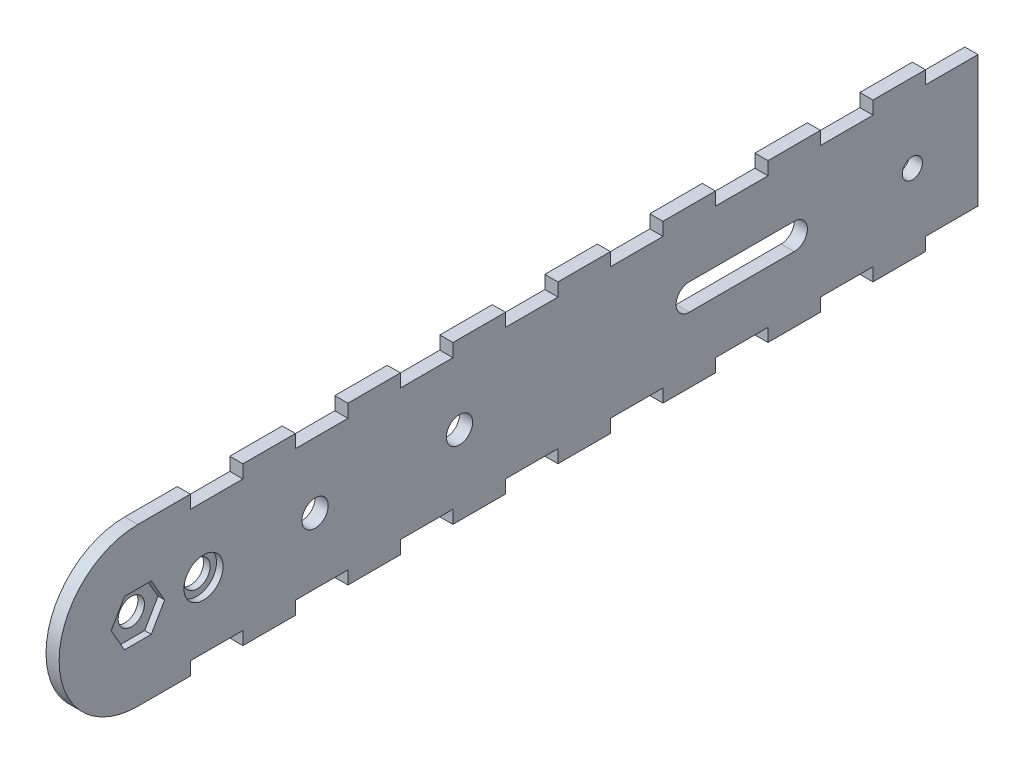
SolidWorks part; units mm, degrees
material "Acrylic (Medium-high impact)"
ref_plane "Front Plane" through (0, 0, 0) normal (0, 0, 1) x (1, 0, 0)
ref_plane "Top Plane" through (0, 0, 0) normal (0, 1, 0) x (1, 0, 0)
ref_plane "Right Plane" through (0, 0, 0) normal (1, 0, 0) x (0, 0, -1)
sketch "Sketch1" plane through (0, 0, 0) normal (1, 0, 0) x (0, 0, -1)
  line L0 (0, 19.05) -> (203.2, 19.05)
  line L1 (0, -19.05) -> (203.2, -19.05)
  line L2 (203.2, -19.05) -> (203.2, 19.05)
  line L3 (203.2, 0) -> (7.9375, 0) construction
  line L4 (203.2, 19.05) -> (190.5, 19.05)
  line L5 (203.2, 19.05) -> (203.2, 15.875)
  line L6 (203.2, 15.875) -> (190.5, 15.875)
  line L7 (190.5, 19.05) -> (190.5, 15.875)
  line L8 (190.5, -19.05) -> (190.5, -15.875)
  line L9 (203.2, -15.875) -> (190.5, -15.875)
  line L10 (203.2, -19.05) -> (203.2, -15.875)
  line L11 (165.1, 19.05) -> (165.1, 15.875)
  line L12 (165.1, -19.05) -> (165.1, -15.875)
  line L13 (177.8, -15.875) -> (165.1, -15.875)
  line L14 (177.8, 15.875) -> (165.1, 15.875)
  line L15 (177.8, 19.05) -> (177.8, 15.875)
  line L16 (177.8, -19.05) -> (177.8, -15.875)
  line L17 (139.7, 19.05) -> (139.7, 15.875)
  line L18 (139.7, -19.05) -> (139.7, -15.875)
  line L19 (152.4, -15.875) -> (139.7, -15.875)
  line L20 (152.4, 15.875) -> (139.7, 15.875)
  line L21 (152.4, 19.05) -> (152.4, 15.875)
  line L22 (152.4, -19.05) -> (152.4, -15.875)
  line L23 (114.3, 19.05) -> (114.3, 15.875)
  line L24 (114.3, -19.05) -> (114.3, -15.875)
  line L25 (127, -15.875) -> (114.3, -15.875)
  line L26 (127, 15.875) -> (114.3, 15.875)
  line L27 (127, 19.05) -> (127, 15.875)
  line L28 (127, -19.05) -> (127, -15.875)
  line L29 (88.9, 19.05) -> (88.9, 15.875)
  line L30 (88.9, -19.05) -> (88.9, -15.875)
  line L31 (101.6, -15.875) -> (88.9, -15.875)
  line L32 (101.6, 15.875) -> (88.9, 15.875)
  line L33 (101.6, 19.05) -> (101.6, 15.875)
  line L34 (101.6, -19.05) -> (101.6, -15.875)
  line L35 (63.5, 19.05) -> (63.5, 15.875)
  line L36 (63.5, -19.05) -> (63.5, -15.875)
  line L37 (76.2, -15.875) -> (63.5, -15.875)
  line L38 (76.2, 15.875) -> (63.5, 15.875)
  line L39 (76.2, 19.05) -> (76.2, 15.875)
  line L40 (76.2, -19.05) -> (76.2, -15.875)
  line L41 (38.1, 19.05) -> (38.1, 15.875)
  line L42 (38.1, -19.05) -> (38.1, -15.875)
  line L43 (50.8, -15.875) -> (38.1, -15.875)
  line L44 (50.8, 15.875) -> (38.1, 15.875)
  line L45 (50.8, 19.05) -> (50.8, 15.875)
  line L46 (50.8, -19.05) -> (50.8, -15.875)
  line L47 (12.7, 19.05) -> (12.7, 15.875)
  line L48 (12.7, -19.05) -> (12.7, -15.875)
  line L49 (25.4, -15.875) -> (12.7, -15.875)
  line L50 (25.4, 15.875) -> (12.7, 15.875)
  line L51 (25.4, 19.05) -> (25.4, 15.875)
  line L52 (25.4, -19.05) -> (25.4, -15.875)
  circle A0 centre (0, 0) radius 3.175
  arc A1 (0, 19.05) -> (0, -19.05) centre (0, 0) ccw
  dimension "D1" = 6.35
  dimension "D2" = 38.1
  dimension "D3" = 203.2
  dimension "D4" = 3.175
  dimension "D5" = 12.7
  dimension "D7" = 12.7
  dimension "D8" = 195.2625
  dimension "D6" = 8
extrude "Boss-Extrude1" add sketch "Sketch1" along normal blind 3.175
sketch "Sketch2" plane through (3.175, 0, 0) normal (1, 0, 0) x (0, 0, -1)
  line L0 (15.875, 0) -> (0, 0) construction
  line L1 (203.2, 0) -> (187.325, 0) construction
  line L2 (203.2, -15.875) -> (203.2, 15.875) construction
  line L3 (42.8625, 0) -> (77.7875, 0) construction
  line L4 (-19.05, 0) -> (203.2, 0) construction
  circle A0 centre (0, 0) radius 7.9375 construction
  circle A1 centre (15.875, 0) radius 7.9375 construction
  circle A2 centre (15.875, 0) radius 3.2004
  circle A5 centre (187.325, 0) radius 2.4384
  circle A6 centre (42.8625, 0) radius 3.175
  circle A7 centre (77.7875, 0) radius 3.175
  arc A8 (0, 19.05) -> (0, -19.05) centre (0, 0) ccw construction
  point P22 (60.325, 0)
  dimension "D1" = 15.875
  dimension "D2" = 6.4008
  dimension "D4" = 4.8768
  dimension "D5" = 6.35
  dimension "D3" = 15.875
  dimension "D6" = 34.925
  dimension "D7" = 127
extrude "Cut-Extrude2" cut sketch "Sketch2" against normal through all
sketch "Sketch3" plane through (3.175, 0, 0) normal (1, 0, 0) x (0, 0, -1)
  line L0 (0, 0) -> (0, 5.5944) construction
  line L1 (3.2299, -5.5943) -> (6.4598, 0)
  line L2 (6.4598, 0) -> (3.2299, 5.5944)
  line L3 (3.2299, 5.5944) -> (-3.2299, 5.5944)
  line L4 (-3.2299, 5.5944) -> (-6.4598, 0)
  line L5 (-6.4598, 0) -> (-3.2299, -5.5943)
  line L6 (-3.2299, -5.5943) -> (3.2299, -5.5943)
  line L7 (12.7, 19.05) -> (12.7, 15.875) construction
  circle A0 centre (0, 0) radius 5.5943 construction
  circle A1 centre (15.875, 0) radius 4.7307
  circle A2 centre (15.875, 0) radius 3.2004 construction
  dimension "D2" = 9.4615
  dimension "D1" = 11.1887
extrude "Cut-Extrude3" cut sketch "Sketch3" against normal blind 1.5875
sketch "Sketch4" plane through (3.175, 0, 0) normal (1, 0, 0) x (0, 0, -1)
  line L0 (133.35, 3.175) -> (158.75, 3.175)
  line L1 (158.75, -3.175) -> (133.35, -3.175)
  line L2 (133.35, 0) -> (158.75, 0) construction
  line L3 (152.4, 15.875) -> (139.7, 15.875) construction
  line L4 (203.2, -15.875) -> (203.2, 15.875) construction
  arc A0 (158.75, 3.175) -> (158.75, -3.175) centre (158.75, 0) cw
  arc A1 (133.35, -3.175) -> (133.35, 3.175) centre (133.35, 0) cw
  point P6 (146.05, 0)
  point P9 (146.05, 15.875)
  point P13 (203.2, 0)
  dimension "D1" = 3.175
  dimension "D2" = 25.4
extrude "Cut-Extrude4" cut sketch "Sketch4" against normal through all
